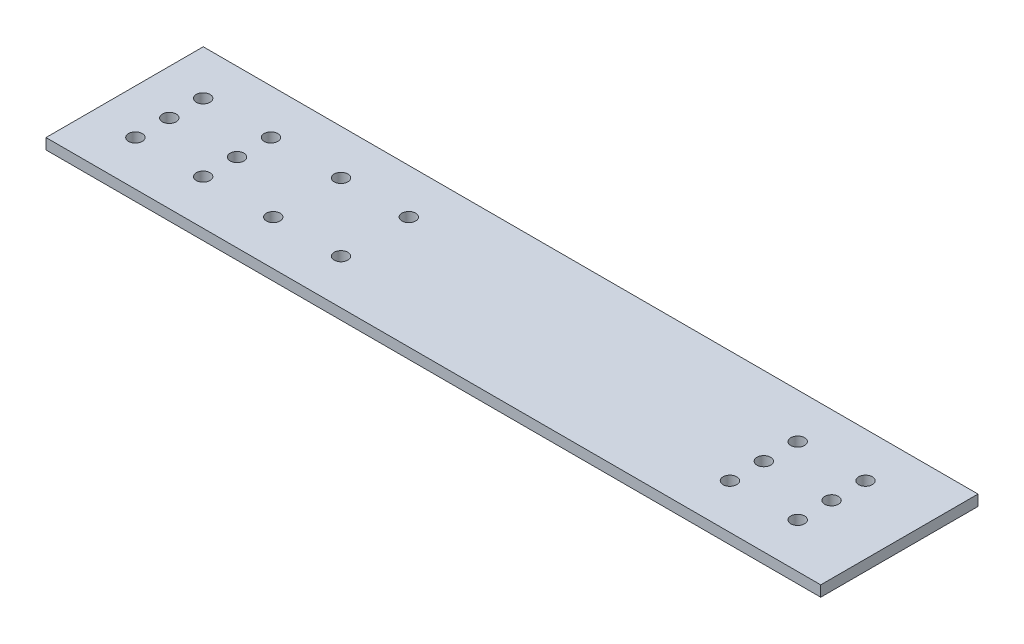
SolidWorks part; units mm, degrees
ref_plane "Front Plane" through (0, 0, 0) normal (0, 0, 1) x (1, 0, 0)
ref_plane "Top Plane" through (0, 0, 0) normal (0, 1, 0) x (1, 0, 0)
ref_plane "Right Plane" through (0, 0, 0) normal (1, 0, 0) x (0, 0, -1)
sketch "Sketch1" plane through (0, 0, 0) normal (0, 1, 0) x (1, 0, 0)
  line L0 (-46.35, 46.4) -> (410.85, 46.4)
  line L1 (-20, 20) -> (20, 20) construction
  line L2 (-20, 20) -> (-20, -20) construction
  line L3 (-20, -20) -> (20, -20) construction
  line L4 (20, 20) -> (20, -20) construction
  line L5 (-20, 20) -> (20, -20) construction
  line L6 (-20, -20) -> (20, 20) construction
  line L8 (-46.35, 46.4) -> (-46.35, -46.4)
  line L11 (410.85, 46.4) -> (410.85, -46.4)
  line L12 (410.85, -46.4) -> (-46.35, -46.4)
  line L13 (350.85, 0) -> (0, 0) construction
  line L14 (370.85, -20) -> (330.85, -20) construction
  line L15 (370.85, -20) -> (370.85, 20) construction
  line L16 (370.85, 20) -> (330.85, 20) construction
  line L17 (330.85, -20) -> (330.85, 20) construction
  line L18 (370.85, -20) -> (330.85, 20) construction
  line L19 (370.85, 20) -> (330.85, -20) construction
  line L20 (81.35, 0) -> (81.35, 30.8998) construction
  line L25 (-40, 40) -> (40, 40) construction
  line L26 (310.85, -40) -> (390.85, -40) construction
  line L31 (-40, 40) -> (-40, -40) construction
  line L32 (-40, -40) -> (40, -40) construction
  line L33 (310.85, -40) -> (310.85, 40) construction
  line L34 (310.85, 40) -> (390.85, 40) construction
  line L35 (390.85, -40) -> (390.85, 40) construction
  line L36 (310.85, -40) -> (390.85, 40) construction
  line L37 (310.85, 40) -> (390.85, -40) construction
  line L38 (278.85, -20) -> (238.85, -20) construction
  line L39 (278.85, -20) -> (278.85, 20) construction
  line L40 (278.85, 20) -> (238.85, 20) construction
  line L41 (238.85, -20) -> (238.85, 20) construction
  line L42 (278.85, -20) -> (238.85, 20) construction
  line L43 (278.85, 20) -> (238.85, -20) construction
  line L48 (40, 40) -> (40, -40) construction
  line L49 (-40, 40) -> (40, -40) construction
  line L50 (-40, -40) -> (40, 40) construction
  line L51 (61.35, -20) -> (101.35, -20) construction
  line L52 (61.35, -20) -> (61.35, 20) construction
  line L53 (61.35, 20) -> (101.35, 20) construction
  line L54 (101.35, -20) -> (101.35, 20) construction
  line L55 (61.35, -20) -> (101.35, 20) construction
  line L56 (61.35, 20) -> (101.35, -20) construction
  line L57 (46.35, 30.8998) -> (116.35, 30.8998) construction
  line L58 (46.35, 30.8998) -> (46.35, -40.05) construction
  line L59 (46.35, -40.05) -> (116.35, -40.05) construction
  line L60 (116.35, 30.8998) -> (116.35, -40.05) construction
  circle A0 centre (-20, 20) radius 4.05
  circle A1 centre (20, 20) radius 4.05
  circle A2 centre (20, -20) radius 4.05
  circle A3 centre (-20, -20) radius 4.05
  circle A4 centre (-20, 0) radius 4.05
  circle A5 centre (20, 0) radius 4.05
  circle A6 centre (330.85, 20) radius 4.05
  circle A8 centre (370.85, 20) radius 4.05
  circle A9 centre (370.85, -20) radius 4.05
  circle A11 centre (330.85, -20) radius 4.05
  circle A20 centre (330.85, 0) radius 4.05
  circle A21 centre (370.85, 0) radius 4.05
  circle A22 centre (278.85, -20) radius 4.05 construction
  circle A23 centre (278.85, 20) radius 4.05 construction
  circle A24 centre (238.85, 20) radius 4.05 construction
  circle A25 centre (238.85, -20) radius 4.05 construction
  circle A26 centre (61.35, 20) radius 4.05
  circle A27 centre (101.35, 20) radius 4.05
  circle A28 centre (101.35, -20) radius 4.05
  circle A29 centre (61.35, -20) radius 4.05
  point P0 (0, 0)
  point P15 (350.85, 0)
  point P29 (258.85, 0)
  point P38 (81.35, 0)
  dimension "D2" = 8.1
  dimension "D8" = 6.35
  dimension "D9" = 46.35
  dimension "D15" = 8.1
  dimension "D18" = 8.1
  dimension "D1" = 40
  dimension "D3" = 80
  dimension "D4" = 46.4
  dimension "D5" = 46.4
  dimension "D6" = 60
  dimension "D7" = 350.85
  dimension "D10" = 40
  dimension "D11" = 80
  dimension "D12" = 80
  dimension "D13" = 40
  dimension "D14" = 40
  dimension "D16" = 32
  dimension "D17" = 457.2
  dimension "D19" = 6.35
  dimension "D20" = 70
  dimension "D21" = 6.35
extrude "Boss-Extrude1" add sketch "Sketch1" along normal blind 6.35
